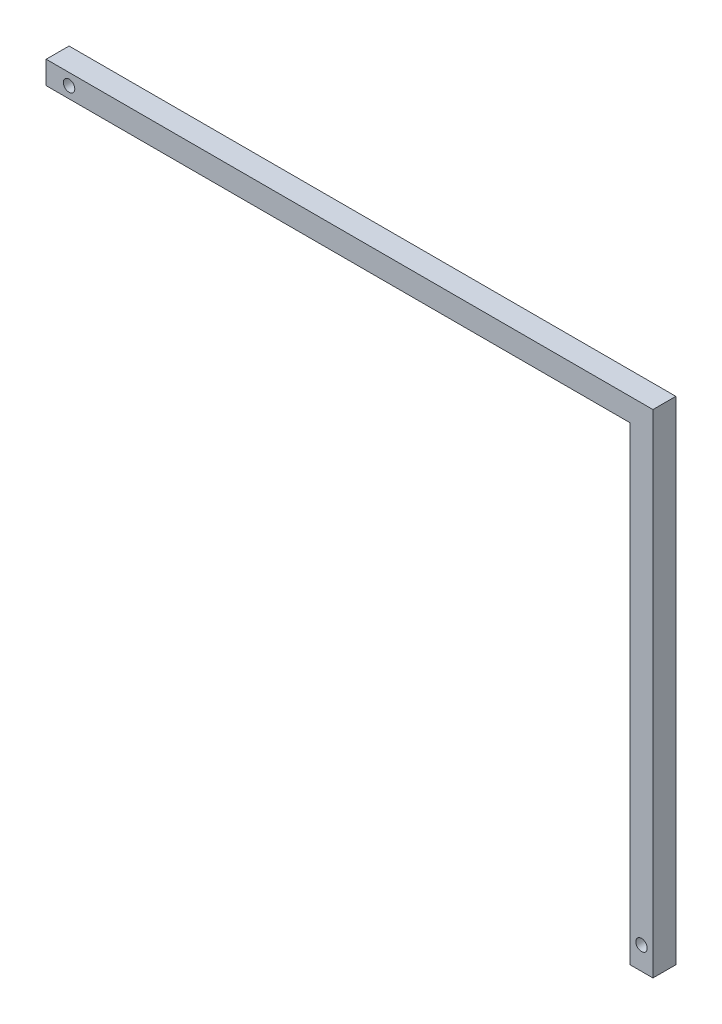
SolidWorks part; units mm, degrees
ref_plane "Спереди" through (0, 0, 0) normal (0, 0, 1) x (1, 0, 0)
ref_plane "Сверху" through (0, 0, 0) normal (0, 1, 0) x (1, 0, 0)
ref_plane "Справа" through (0, 0, 0) normal (1, 0, 0) x (0, 0, -1)
sketch "Эскиз1" plane through (0, 0, 0) normal (0, 0, 1) x (1, 0, 0)
  line L1 (-265, -10) -> (265, -10)
  line L2 (-265, -10) -> (-265, 10)
  line L3 (-265, 10) -> (265, 10)
  line L4 (265, -10) -> (265, 10)
  line L5 (-265, -10) -> (265, 10) construction
  line L6 (-265, 10) -> (265, -10) construction
  line L7 (265, 10) -> (245, 10)
  line L8 (265, 10) -> (265, -420)
  line L9 (265, -420) -> (245, -420)
  line L10 (245, 10) -> (245, -420)
  circle A0 centre (-245, 0) radius 5
  point P0 (0, 0)
  dimension "D5" = 10
  dimension "D1" = 20
  dimension "D2" = 530
  dimension "D3" = 20
  dimension "D4" = 430
  dimension "D6" = 20
  dimension "D7" = 10
extrude "Бобышка-Вытянуть1" add sketch "Эскиз1" along normal blind 20 contours L4 L1 L2 L3 | L7 L10 L9 L8 | A0
sketch "Эскиз2" plane through (0, 0, 20) normal (0, 0, 1) x (1, 0, 0)
  line L0 (265, -420) -> (245, -420) construction
  line L1 (265, -420) -> (265, 10) construction
  circle A0 centre (255, -400) radius 5
  dimension "D1" = 10
  dimension "D2" = 20
  dimension "D3" = 10
extrude "Вырез-Вытянуть1" cut sketch "Эскиз2" against normal blind 20
